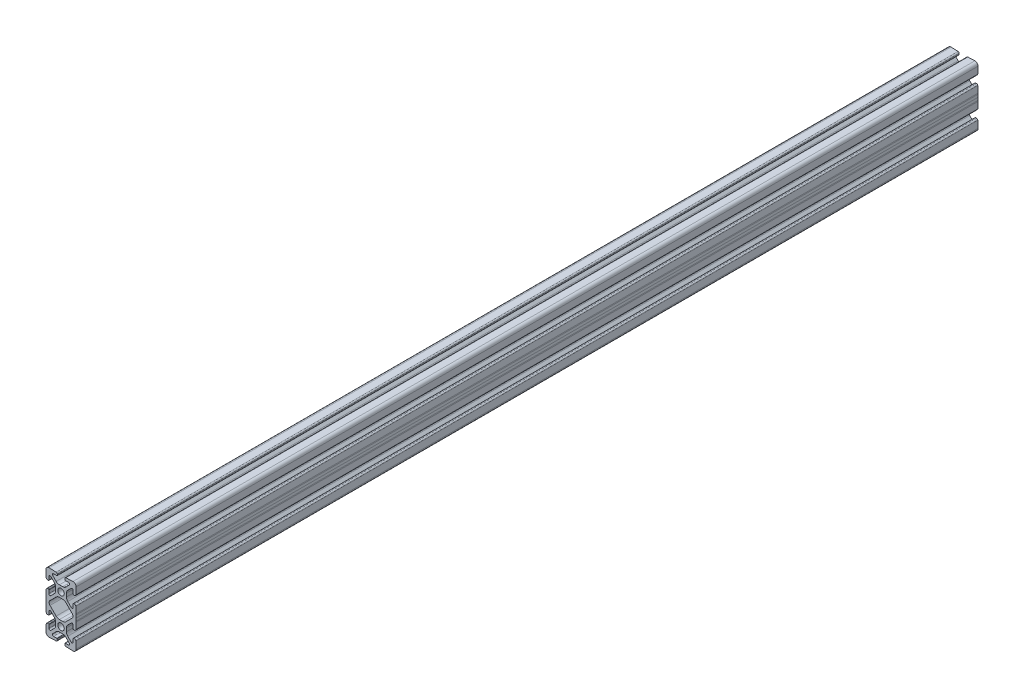
SolidWorks part; units mm, degrees
ref_plane "Front Plane" through (0, 0, 0) normal (0, 0, 1) x (1, 0, 0)
ref_plane "Top Plane" through (0, 0, 0) normal (0, 1, 0) x (1, 0, 0)
ref_plane "Right Plane" through (0, 0, 0) normal (1, 0, 0) x (0, 0, -1)
sketch "Sketch1" plane through (0, 0, 0) normal (0, 0, 1) x (1, 0, 0)
  line L0 (0, 10) -> (0, 20) construction
  line L1 (0, 10) -> (10, 10) construction
  line L2 (0, 10) -> (-10, 20) construction
  line L3 (-7.9302, 19.9988) -> (-3.2721, 19.8361)
  line L4 (-10, 20) -> (0, 20) construction
  line L6 (-2.8352, 18.0198) -> (-4.953, 18.0937)
  line L10 (0, 13.6) -> (-1.1022, 13.6)
  line L11 (-3.2236, 14.4787) -> (-5.5244, 16.7796)
  line L24 (0, 10) -> (-10, 10) construction
  line L25 (-10, 10) -> (0, 10) construction
  line L27 (-10, 0) -> (-10, 20) construction
  line L28 (0, 20) -> (10, 20) construction
  line L29 (-2.5249, 18.3091) -> (-2.5005, 19.0087)
  line L30 (-10, -20) -> (10, -20) construction
  line L31 (0, 20) -> (0, -20) construction
  arc A0 (-9.4142, 19.4142) -> (-7.9302, 19.9988) centre (-8, 18) cw
  arc A5 (-3.2721, 19.8361) -> (-2.5005, 19.0087) centre (-3.3, 19.0366) cw
  arc A6 (-1.1022, 13.6) -> (-3.2236, 14.4787) centre (-1.1022, 16.6) cw
  circle A16 centre (0, 10) radius 2.15
  arc A18 (-5.5244, 16.7796) -> (-4.953, 18.0937) centre (-4.9799, 17.3241) cw
  arc A20 (-2.8352, 18.0198) -> (-2.5249, 18.3091) centre (-2.8247, 18.3196) ccw
  point P15 (0, -20)
  point P24 (0, 0)
  point P42 (-2.3449, 13.6)
  point P80 (-10, 10)
  dimension "D11" = 2
  dimension "D15" = 3
  dimension "Center Hole Diameter" = 4.3
  dimension "D7" = 0.8
  dimension "D8" = 0.3
  dimension "D4" = 0.7701
  dimension "D1" = 45
  dimension "D2" = 2
  dimension "Rail Width" = 20
  dimension "T-Slot Depth" = 6.4
  dimension "D9" = 1.8
  dimension "D23" = 7.2
  dimension "D5" = 11.5
  dimension "T-Slot Width" = 5
  dimension "D3" = 1.775
  dimension "D6" = 9.9598
  dimension "Rail Height" = 40
sketch "Sketch2" plane through (0, 0, 0) normal (1, 0, 0) x (0, 0, -1)
  line L0 (-1524, 0) -> (1524, 0)
  line L1 (-1524, -20) -> (-1524, 20)
  line L2 (0, 10) -> (0, 20) construction
  line L3 (0, 0) -> (0, 20) construction
  line L4 (1524, -20) -> (1524, 20)
  line L5 (-10, 10) -> (10, 10) construction
  point P0 (-1491.5, 0)
  point P3 (0, 0)
  point P7 (1491.5, 0)
  point P11 (-1524, 0)
  point P14 (1524, 0)
  point P23 (0, 10)
  dimension "D1" = 32.5
  dimension "Length" = 3048
sketch "Sketch3" plane through (0, 0, 0) normal (0, 0, 1) x (1, 0, 0)
  line L0 (-2.5249, 18.3091) -> (-2.5005, 19.0087) construction
  line L1 (0, 10) -> (-10, 20) construction
  line L2 (0, 10) -> (-10, 20) construction
  line L5 (-7.9302, 19.9988) -> (-3.2721, 19.8361) construction
  line L6 (-2.8352, 18.0198) -> (-4.953, 18.0937) construction
  line L7 (-8.3091, 7.4751) -> (-9.0087, 7.4995)
  line L17 (-2.5249, 18.3091) -> (-2.5005, 19.0087)
  line L19 (-2.8352, 18.0198) -> (-4.953, 18.0937)
  line L21 (-3.6, 10) -> (0, 10) construction
  line L22 (-3.6, 8.8978) -> (-3.6, 11.1022)
  line L23 (-4.4787, 13.2236) -> (-6.7796, 15.5244)
  line L42 (-3.2236, 14.4787) -> (-5.5244, 16.7796) construction
  line L43 (0, 13.6) -> (-1.1022, 13.6) construction
  line L44 (-7.9302, 19.9988) -> (-3.2721, 19.8361)
  line L47 (-3.2236, 14.4787) -> (-5.5244, 16.7796)
  line L48 (1.1022, 13.6) -> (-1.1022, 13.6)
  line L59 (0, 13.6) -> (0, 12.15) construction
  line L60 (-9.9988, 17.9302) -> (-9.8361, 13.2721)
  line L61 (-8.0198, 12.8352) -> (-8.0937, 14.953)
  line L62 (-8.3091, 12.5249) -> (-9.0087, 12.5005)
  line L63 (-8.0198, 7.1648) -> (-8.0937, 5.047)
  line L64 (-9.9868, 2.4128) -> (-9.8361, 6.7279)
  line L65 (1.1022, 6.4) -> (-1.1022, 6.4)
  line L66 (-3.2236, 5.5213) -> (-7.3307, 1.4142)
  line L68 (-4.4787, 6.7764) -> (-6.7796, 4.4756)
  line L73 (10, 0) -> (-10, 0) construction
  line L75 (-10, 0) -> (-9.999, 1.7266)
  line L77 (10, 0) -> (9.999, 1.7266)
  line L78 (4.4787, 6.7764) -> (6.7796, 4.4756)
  line L79 (3.2236, 5.5213) -> (7.3307, 1.4142)
  line L81 (9.9868, 2.4128) -> (9.8361, 6.7279)
  line L82 (8.0198, 7.1648) -> (8.0937, 5.047)
  line L83 (8.3091, 12.5249) -> (9.0087, 12.5005)
  line L84 (8.0198, 12.8352) -> (8.0937, 14.953)
  line L85 (9.9988, 17.9302) -> (9.8361, 13.2721)
  line L87 (3.2236, 14.4787) -> (5.5244, 16.7796)
  line L88 (7.9302, 19.9988) -> (3.2721, 19.8361)
  line L89 (4.4787, 13.2236) -> (6.7796, 15.5244)
  line L90 (3.6, 8.8978) -> (3.6, 11.1022)
  line L91 (2.8352, 18.0198) -> (4.953, 18.0937)
  line L92 (2.5249, 18.3091) -> (2.5005, 19.0087)
  line L93 (8.3091, 7.4751) -> (9.0087, 7.4995)
  line L94 (-10, 0) -> (-7.9165, 0)
  line L96 (7.9165, 0) -> (10, 0)
  arc A0 (-7.9302, 19.9988) -> (-9.4142, 19.4142) centre (-8, 18) ccw construction
  arc A1 (-2.8352, 18.0198) -> (-2.5249, 18.3091) centre (-2.8247, 18.3196) ccw construction
  arc A3 (-2.8352, 18.0198) -> (-2.5249, 18.3091) centre (-2.8247, 18.3196) ccw
  arc A5 (-7.9302, 19.9988) -> (-9.9988, 17.9302) centre (-8, 18) ccw
  arc A10 (-3.2236, 5.5213) -> (-1.1022, 6.4) centre (-1.1022, 3.4) cw
  circle A13 centre (0, 10) radius 2.15 construction
  circle A14 centre (0, 10) radius 2.15
  arc A15 (-4.4787, 13.2236) -> (-3.6, 11.1022) centre (-6.6, 11.1022) cw
  arc A16 (-8.0937, 14.953) -> (-6.7796, 15.5244) centre (-7.3241, 14.9799) cw
  arc A17 (-9.0087, 12.5005) -> (-9.8361, 13.2721) centre (-9.0366, 13.3) cw
  arc A18 (-8.0198, 12.8352) -> (-8.3091, 12.5249) centre (-8.3196, 12.8247) cw
  arc A36 (-2.5005, 19.0087) -> (-3.2721, 19.8361) centre (-3.3, 19.0366) ccw construction
  arc A38 (-4.953, 18.0937) -> (-5.5244, 16.7796) centre (-4.9799, 17.3241) ccw construction
  arc A39 (-3.2236, 14.4787) -> (-1.1022, 13.6) centre (-1.1022, 16.6) ccw construction
  arc A41 (-2.5005, 19.0087) -> (-3.2721, 19.8361) centre (-3.3, 19.0366) ccw
  arc A43 (-4.953, 18.0937) -> (-5.5244, 16.7796) centre (-4.9799, 17.3241) ccw
  arc A44 (-3.2236, 14.4787) -> (-1.1022, 13.6) centre (-1.1022, 16.6) ccw
  arc A47 (-8.0198, 7.1648) -> (-8.3091, 7.4751) centre (-8.3196, 7.1753) ccw
  arc A48 (-9.0087, 7.4995) -> (-9.8361, 6.7279) centre (-9.0366, 6.7) ccw
  arc A49 (-8.0937, 5.047) -> (-6.7796, 4.4756) centre (-7.3241, 5.0201) ccw
  arc A50 (-4.4787, 6.7764) -> (-3.6, 8.8978) centre (-6.6, 8.8978) ccw
  arc A54 (-7.9165, 0) -> (-7.3307, 1.4142) centre (-5.9165, 0) cw
  arc A55 (-9.999, 1.7266) -> (-9.9868, 2.4128) centre (10.001, 1.7148) cw
  arc A56 (9.999, 1.7266) -> (9.9868, 2.4128) centre (-10.001, 1.7148) ccw
  arc A57 (7.9165, 0) -> (7.3307, 1.4142) centre (5.9165, 0) ccw
  arc A58 (4.4787, 6.7764) -> (3.6, 8.8978) centre (6.6, 8.8978) cw
  arc A59 (8.0937, 5.047) -> (6.7796, 4.4756) centre (7.3241, 5.0201) cw
  arc A60 (9.0087, 7.4995) -> (9.8361, 6.7279) centre (9.0366, 6.7) cw
  arc A61 (8.0198, 7.1648) -> (8.3091, 7.4751) centre (8.3196, 7.1753) cw
  arc A62 (3.2236, 14.4787) -> (1.1022, 13.6) centre (1.1022, 16.6) cw
  arc A63 (4.953, 18.0937) -> (5.5244, 16.7796) centre (4.9799, 17.3241) cw
  arc A64 (2.5005, 19.0087) -> (3.2721, 19.8361) centre (3.3, 19.0366) cw
  arc A65 (8.0198, 12.8352) -> (8.3091, 12.5249) centre (8.3196, 12.8247) ccw
  arc A66 (9.0087, 12.5005) -> (9.8361, 13.2721) centre (9.0366, 13.3) ccw
  arc A67 (8.0937, 14.953) -> (6.7796, 15.5244) centre (7.3241, 14.9799) ccw
  arc A68 (4.4787, 13.2236) -> (3.6, 11.1022) centre (6.6, 11.1022) ccw
  arc A70 (3.2236, 5.5213) -> (1.1022, 6.4) centre (1.1022, 3.4) ccw
  arc A71 (7.9302, 19.9988) -> (9.9988, 17.9302) centre (8, 18) cw
  arc A72 (2.8352, 18.0198) -> (2.5249, 18.3091) centre (2.8247, 18.3196) cw
  point P59 (-9.9988, 2.0698)
  point P71 (0, 0)
  point P116 (0, 6.4)
  dimension "D1" = 20
extrude "Boss-Extrude1" add sketch "Sketch3" along normal mid plane 3048
pattern_circular "CirPattern1" count 2 over 360 about axis through (0, 0, 0) along (0, 0, 1) of "Boss-Extrude1"
ref_plane "Contact Plane 1" through (0, 20, 0) normal (0, 1, 0) x (1, 0, 0)
ref_plane "Contact Plane 2" through (10, 10, 0) normal (1, 0, 0) x (0, 0, -1)
ref_plane "Contact Plane 3" through (0, -20, 0) normal (0, -1, 0) x (-1, 0, 0)
ref_plane "Contact Plane 4" through (-10, 10, 0) normal (-1, 0, 0) x (0, 0, 1)
sketch "Sketch4" plane through (3.6, 0, 0) normal (1, 0, 0) x (0, 0, -1)
  line L0 (-1524, -20) -> (1524, -20) construction
  line L1 (-1524, 20) -> (-924, 20)
  line L2 (-1524, 20) -> (-1524, -20)
  line L3 (-1524, -20) -> (-924, -20)
  line L4 (-924, 20) -> (-924, -20)
extrude "Cut-Extrude1" cut sketch "Sketch4" against normal blind 23 and the other way blind 10 flip side to cut
equation "\"D1@Sketch2\"=\"Rail Width@Sketch1\"*1.625"
equation "\"D1@Boss-Extrude1\" = \"Length@Sketch2\""
equation "\"D1@Sketch3\"=\"Rail Width@Sketch1\""
